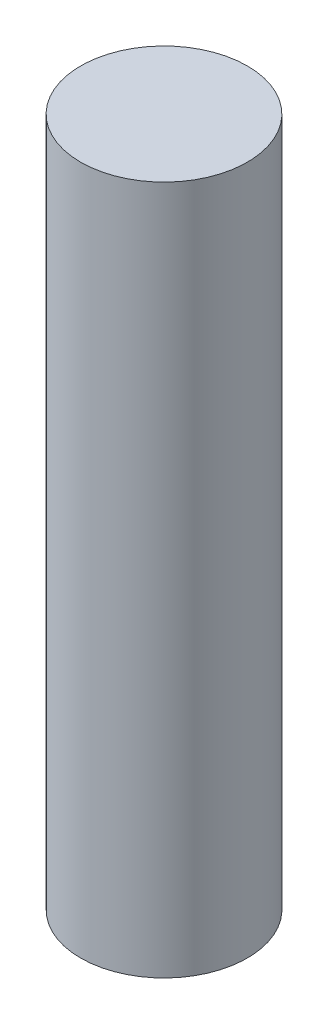
SolidWorks part; units mm, degrees
ref_plane "Front" through (0, 0, 0) normal (0, 0, 1) x (1, 0, 0)
ref_plane "Top" through (0, 0, 0) normal (0, 1, 0) x (1, 0, 0)
ref_plane "Right" through (0, 0, 0) normal (1, 0, 0) x (0, 0, -1)
sketch "Sketch1" plane through (0, 0, 0) normal (0, 1, 0) x (1, 0, 0)
  circle A0 centre (0, 0) radius 1.5
  dimension "D1" = 3
extrude "Boss-Extrude1" add sketch "Sketch1" along normal blind 12.4
